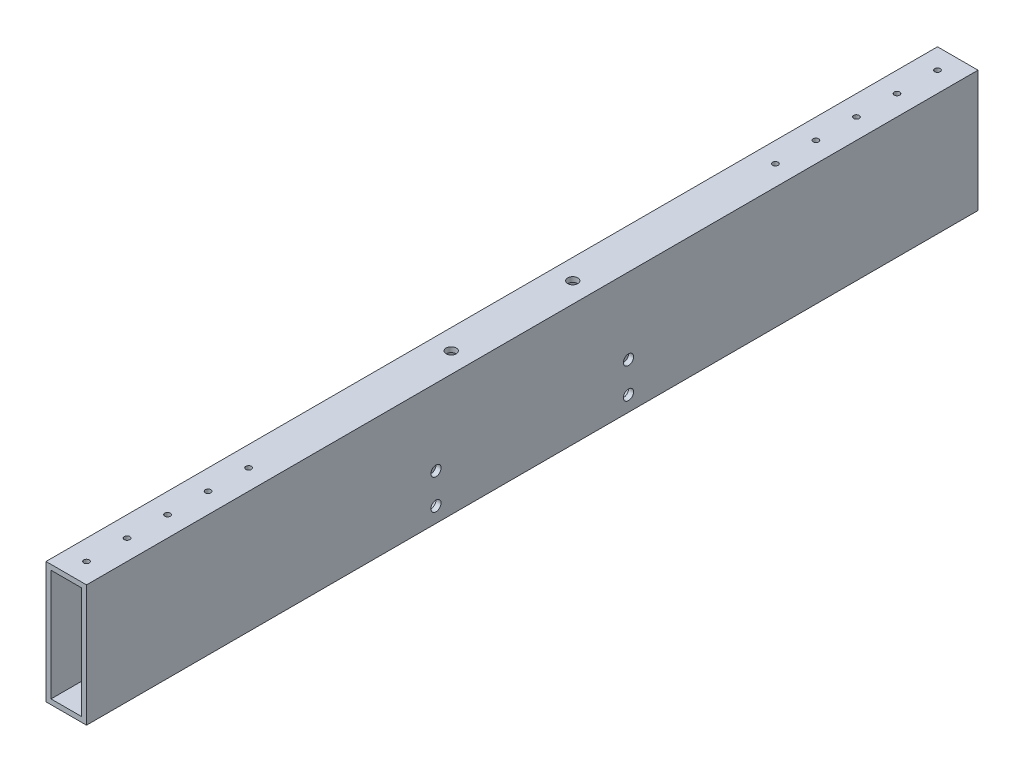
SolidWorks part; units mm, degrees
material "6061-T6 (SS)"
ref_plane "Front Plane" through (0, 0, 0) normal (0, 0, 1) x (1, 0, 0)
ref_plane "Top Plane" through (0, 0, 0) normal (0, 1, 0) x (1, 0, 0)
ref_plane "Right Plane" through (0, 0, 0) normal (1, 0, 0) x (0, 0, -1)
sketch "Sketch1" plane through (0, 0, 0) normal (0, 0, 1) x (1, 0, 0)
  line L0 (9.525, 34.925) -> (-9.525, 34.925)
  line L1 (12.7, 38.1) -> (-12.7, 38.1)
  line L2 (12.7, 38.1) -> (12.7, -38.1)
  line L3 (12.7, -38.1) -> (-12.7, -38.1)
  line L4 (-12.7, 38.1) -> (-12.7, -38.1)
  line L5 (12.7, 38.1) -> (-12.7, -38.1) construction
  line L6 (12.7, -38.1) -> (-12.7, 38.1) construction
  line L7 (-9.525, 34.925) -> (-9.525, -34.925)
  line L8 (9.525, -34.925) -> (-9.525, -34.925)
  line L9 (9.525, 34.925) -> (9.525, -34.925)
  point P0 (0, 0)
  dimension "D1" = 76.2
  dimension "D2" = 25.4
  dimension "D3" = 3.175
extrude "Boss-Extrude1" add sketch "Sketch1" along normal mid plane 558.8
sketch "Sketch2" plane through (0, 38.1, 0) normal (0, 1, 0) x (1, 0, 0)
  line L1 (12.7, 279.4) -> (-12.7, 279.4) construction
  circle A0 centre (0, 266.7) radius 1.7272
  circle A1 centre (0, 241.3) radius 1.7272
  circle A2 centre (0, 215.9) radius 1.7272
  circle A3 centre (0, 190.5) radius 1.7272
  circle A8 centre (0, 165.1) radius 1.7272
  dimension "D1" = 3.4544
  dimension "D2" = 12.7
  dimension "D3" = 5
sketch "Sketch3" plane through (0, -38.1, 0) normal (0, -1, 0) x (1, 0, 0)
  line L2 (9.525, 279.4) -> (-9.525, 279.4) construction
  circle A0 centre (0, 254) radius 1.7272
  circle A1 centre (0, 203.2) radius 1.7272
  circle A2 centre (0, 152.4) radius 1.7272
  circle A3 centre (0, 101.6) radius 1.7272
  circle A4 centre (0, 50.8) radius 1.7272
  circle A5 centre (0, 0) radius 1.7272
  circle A6 centre (0, -50.8) radius 1.7272
  circle A7 centre (0, -101.6) radius 1.7272
  circle A8 centre (0, -152.4) radius 1.7272
  circle A9 centre (0, -203.2) radius 1.7272
  circle A10 centre (0, -254) radius 1.7272
  point P6 (0, 279.4)
  dimension "D1" = 3.4544
  dimension "D2" = 25.4
  dimension "D4" = 50.8
  dimension "D3" = 11
extrude "Cut-Extrude2" cut sketch "Sketch3" against normal blind 6.35
hole_wizard "1/4 (0.25) Diameter Hole1" positions "Sketch9" profile "Sketch8" hole size "1/4" standard "ANSI Inch"
sketch "Sketch9" plane through (-12.7, 0, 0) normal (-1, 0, 0) x (0, 0, 1)
  line L0 (-60.325, -28.575) -> (60.325, -28.575) construction
  line L2 (279.4, -38.1) -> (-279.4, -38.1) construction
  line L4 (-127, 0) -> (127, 0) construction
  point P10 (-60.325, -28.575)
  point P11 (60.325, -28.575)
  point P25 (-60.325, -9.525)
  point P27 (60.325, -9.525)
  point P34 (0, -28.575)
  dimension "D1" = 120.65
  dimension "D2" = 9.525
  dimension "D3" = 254
  dimension "D4" = 19.05
  dimension "D5" = 19.05
sketch "Sketch8" plane through (-12.7, -28.575, -60.325) normal (0, 1, 0) x (0, 0, 1)
  line L0 (0, 0) -> (0, 27.3077)
  line L1 (0, 27.3077) -> (3.175, 25.4)
  line L2 (3.175, 25.4) -> (3.175, 0)
  line L5 (3.175, 0) -> (0, 0)
  line L10 (0, 27.3077) -> (-3.175, 25.4) construction
  line L11 (0, -6.35) -> (0, 107.95) construction
  dimension "Hole Dia." = 6.35
  dimension "Hole Depth" = 25.4
  dimension "Drill Angle" = 118
hole_wizard "1/4 (0.25) Diameter Hole2" positions "Sketch12" profile "Sketch13" hole size "1/4" standard "ANSI Inch" end condition through all
sketch "Sketch12" plane through (0, 38.1, 0) normal (0, 1, 0) x (1, 0, 0)
  line L0 (12.7, -279.4) -> (-12.7, -279.4) construction
  line L1 (0, 38.1) -> (0, -38.1) construction
  point P20 (0, -38.1)
  point P22 (0, 38.1)
  point P27 (0, -279.4)
  point P32 (0, 0)
  dimension "D7" = 76.2
sketch "Sketch13" plane through (0, 38.1, 38.1) normal (1, 0, 0) x (0, 0, 1)
  line L0 (0, 0) -> (0, 76.2)
  line L1 (0, 76.2) -> (3.175, 76.2)
  line L2 (3.175, 76.2) -> (3.175, 0)
  line L5 (3.175, 0) -> (0, 0)
  line L11 (0, -6.35) -> (0, 107.95) construction
  dimension "Thru Hole Dia." = 6.35
  dimension "Thru Hole Depth" = 76.2
extrude "Cut-Extrude4" cut sketch "Sketch2" against normal blind 6.35
mirror "Mirror1" about plane through (0, 0, 0) normal (0, 0, 1) of "Cut-Extrude4"
